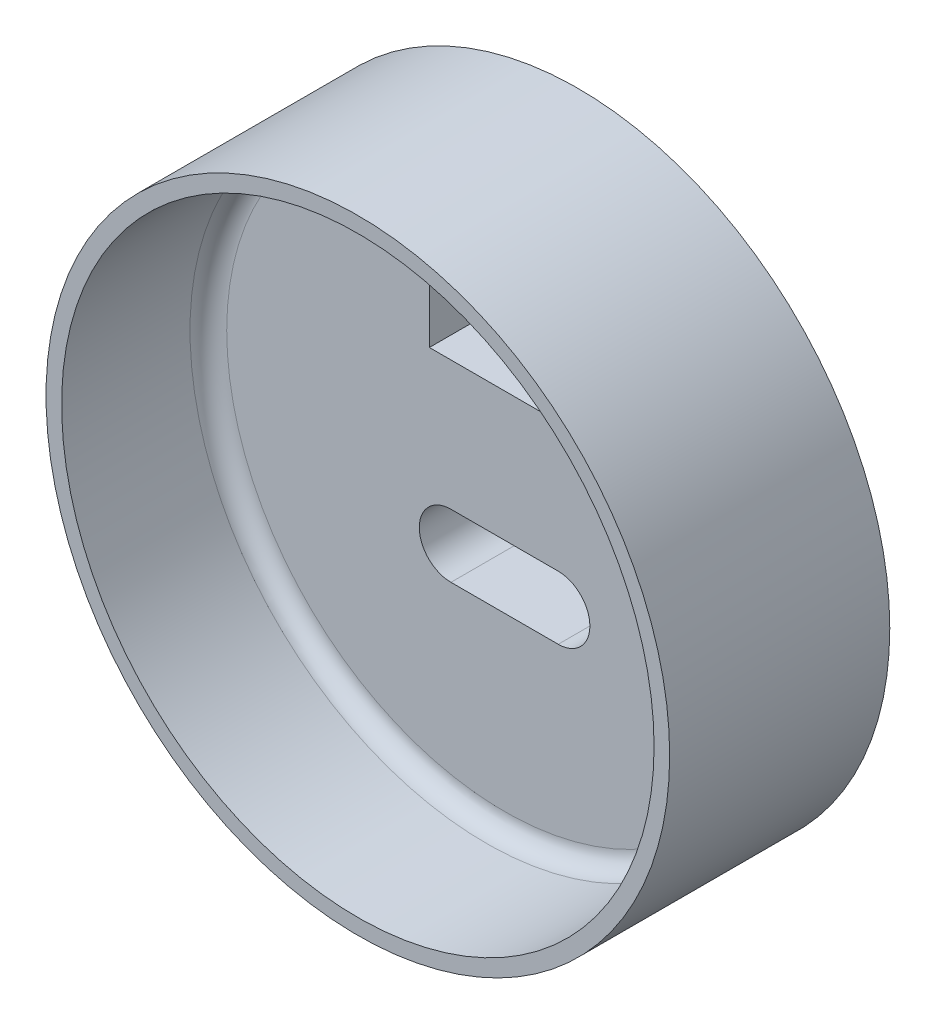
SolidWorks part; units mm, degrees
ref_plane "Front Plane" through (0, 0, 0) normal (0, 0, 1) x (1, 0, 0)
ref_plane "Top Plane" through (0, 0, 0) normal (0, 1, 0) x (1, 0, 0)
ref_plane "Right Plane" through (0, 0, 0) normal (1, 0, 0) x (0, 0, -1)
sketch "Sketch2" plane through (0, 0, 0) normal (0, 0, 1) x (1, 0, 0)
  circle A0 centre (0, 0) radius 17
  dimension "D1" = 34
extrude "Boss-Extrude1" add sketch "Sketch2" along normal blind 12
sketch "Sketch3" plane through (0, 0, 12) normal (0, 0, 1) x (1, 0, 0)
  circle A2 centre (0, 0) radius 16.15
  circle A3 centre (0, 0) radius 10
  dimension "D2" = 20
  dimension "D4" = 32.3
extrude "Cut-Extrude1" cut sketch "Sketch3" against normal blind 8 contours A2 A3 | A3
fillet "Fillet1" radius 1 1 edges at (16.15, 0, 4)
sketch "Sketch4" plane through (0, 0, 0) normal (0, 0, -1) x (-1, 0, 0)
  line L0 (2.925, -4.0618) -> (-2.925, -4.0618) construction
  line L1 (4.1, 4.7127) -> (-4.1, 4.7127)
  line L2 (4.1, 4.7127) -> (4.1, 7.9127)
  line L3 (4.1, 7.9127) -> (-4.1, 7.9127)
  line L4 (-4.1, 4.7127) -> (-4.1, 7.9127)
  line L5 (4.1, 4.7127) -> (-4.1, 7.9127) construction
  line L6 (4.1, 7.9127) -> (-4.1, 4.7127) construction
  line L7 (2.925, -5.7868) -> (-2.925, -5.7868)
  line L8 (2.925, -2.3368) -> (-2.925, -2.3368)
  line L9 (0, 14.2147) -> (0, -8.6544) construction
  arc A0 (2.925, -5.7868) -> (2.925, -2.3368) centre (2.925, -4.0618) ccw
  arc A1 (-2.925, -2.3368) -> (-2.925, -5.7868) centre (-2.925, -4.0618) ccw
  point P0 (0, 6.3127)
  point P7 (0, -4.0618)
  point P19 (-4.65, -4.0618)
  point P20 (4.65, -4.0618)
  dimension "D1" = 8.2
  dimension "D2" = 3.2
  dimension "D3" = 3.45
  dimension "D4" = 9.3
extrude "Cut-Extrude2" cut sketch "Sketch4" against normal through all
